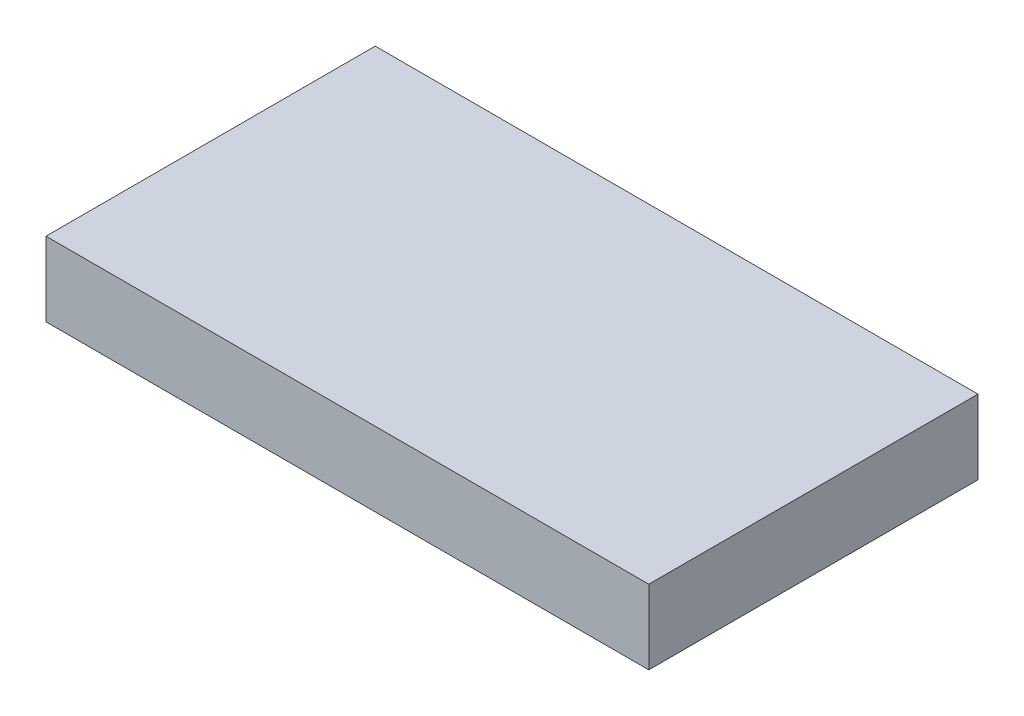
SolidWorks part; units mm, degrees
ref_plane "Front Plane" through (0, 0, 0) normal (0, 0, 1) x (1, 0, 0)
ref_plane "Top Plane" through (0, 0, 0) normal (0, 1, 0) x (1, 0, 0)
ref_plane "Right Plane" through (0, 0, 0) normal (1, 0, 0) x (0, 0, -1)
sketch "Sketch1" plane through (0, 0, 0) normal (0, 1, 0) x (1, 0, 0)
  line L1 (-16.51, -9.017) -> (16.51, -9.017)
  line L2 (-16.51, -9.017) -> (-16.51, 9.017)
  line L3 (-16.51, 9.017) -> (16.51, 9.017)
  line L4 (16.51, -9.017) -> (16.51, 9.017)
  line L5 (-16.51, -9.017) -> (16.51, 9.017) construction
  line L6 (-16.51, 9.017) -> (16.51, -9.017) construction
  point P0 (0, 0)
extrude "Boss-Extrude1" add sketch "Sketch1" along normal blind 4.064
